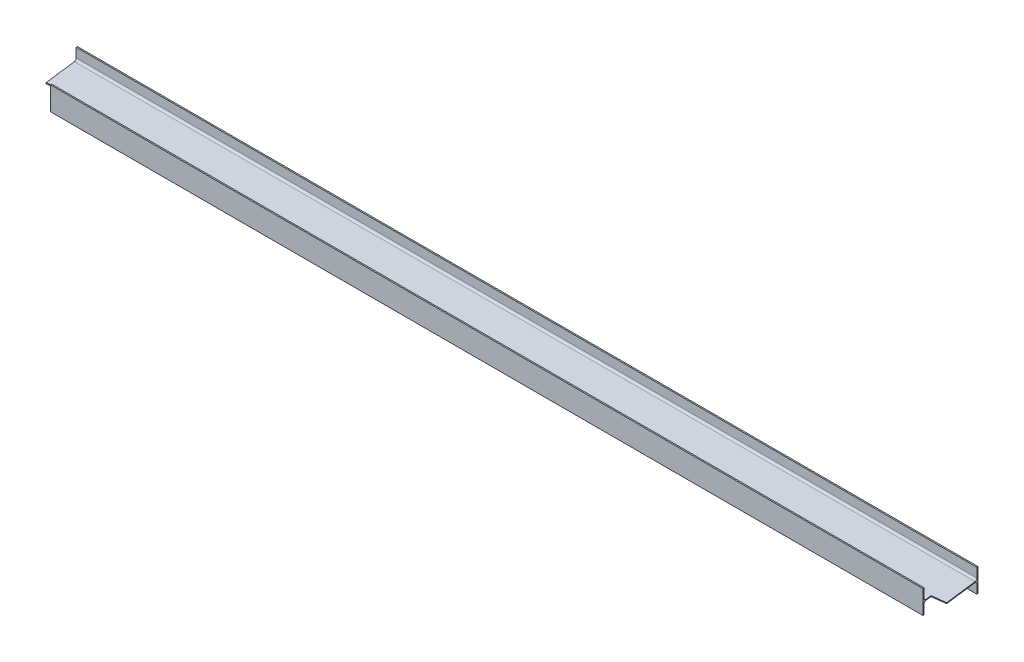
SolidWorks part; units mm, degrees
material "Простая углеродистая сталь"
ref_plane "Спереди" through (0, 0, 0) normal (0, 0, 1) x (1, 0, 0)
ref_plane "Сверху" through (0, 0, 0) normal (0, 1, 0) x (1, 0, 0)
ref_plane "Справа" through (0, 0, 0) normal (1, 0, 0) x (0, 0, -1)
sketch "Эскиз1" plane through (0, 0, 0) normal (0, 0, 1) x (1, 0, 0)
  line L0 (0, 0) -> (5791, 0)
  dimension "D1" = 5791
other "Балочные 30Б1(1)"
ref_plane "Плоскость1" through (0, 0, 0) normal (1, 0, 0) x (0, 1, 0)
sketch "Sketch11" plane through (0, 0, 0) normal (1, 0, 0) x (0, 1, 0)
  line L0 (-126.046, 0) -> (126.046, 0) construction
  line L2 (-15.75, -141) -> (-74.5, -141)
  line L3 (-15.75, 141) -> (-74.5, 141)
  line L4 (-2.75, 128) -> (-2.75, -128)
  line L5 (2.75, 128) -> (2.75, -128)
  line L6 (74.5, -141) -> (74.5, -149)
  line L7 (-74.5, -141) -> (-74.5, -149)
  line L8 (-74.5, 149) -> (-74.5, 141)
  line L9 (74.5, 149) -> (74.5, 141)
  line L10 (74.5, -141) -> (15.75, -141)
  line L11 (74.5, 141) -> (15.75, 141)
  line L12 (74.5, -149) -> (-74.5, -149)
  line L13 (0, 126.046) -> (0, -126.046) construction
  line L14 (74.5, 149) -> (-74.5, 149)
  arc A0 (15.75, 141) -> (2.75, 128) centre (15.75, 128) ccw
  arc A1 (2.75, -128) -> (15.75, -141) centre (15.75, -128) ccw
  arc A2 (-15.75, -141) -> (-2.75, -128) centre (-15.75, -128) ccw
  arc A3 (-2.75, 128) -> (-15.75, 141) centre (-15.75, 128) ccw
  point P9 (0, 0)
  dimension "R, радиус скругления" = 13
  dimension "В, ширина" = 149
  dimension "H, высота" = 298
  dimension "t, толщина полки" = 8
  dimension "S, толщина стенки" = 5.5
sketch "Эскиз3" plane through (0, 74.5, 0) normal (0, 1, 0) x (1, 0, 0)
  line L3 (0, -149) -> (0, 149)
  line L7 (5791, -149) -> (5791, 149)
  line L14 (0, 149) -> (37.25, -149)
  line L15 (5791, -149) -> (0, -149) construction
  line L16 (497.1184, -3860.1965) -> (34.4689, -159) construction
  line L17 (0, -149) -> (37.25, -149)
  line L18 (5791, 149) -> (5753.75, 149)
  line L19 (5791, 149) -> (0, 149) construction
  line L20 (5753.75, 149) -> (5791, -149)
extrude "Вырез-Вытянуть1" cut sketch "Эскиз3" against normal through all
sketch "Эскиз5" plane through (0, 2.75, 0) normal (0, 1, 0) x (1, 0, 0)
  line L0 (28.5676, -79.5405) -> (117.8726, -68.3774)
  line L1 (2.625, 128) -> (34.625, -128) construction
  line L2 (117.8726, -68.3774) -> (127.9504, -149)
  line L3 (5791, -149) -> (37.25, -149) construction
  line L4 (127.9504, -149) -> (37.25, -149)
  line L5 (37.25, -149) -> (28.5676, -79.5405)
  line L6 (5782.3176, -79.5405) -> (5693.0126, -90.7037)
  line L7 (5788.375, -128) -> (5756.375, 128) construction
  line L8 (5693.0126, -90.7037) -> (5700.2996, -149)
  line L9 (5700.2996, -149) -> (5791, -149)
  line L10 (5791, -149) -> (5782.3176, -79.5405)
  dimension "D1" = 90
  dimension "D2" = 70
  dimension "D3" = 70
  dimension "D4" = 90
extrude "Вырез-Вытянуть2" cut sketch "Эскиз5" against normal through all and the other way through all
